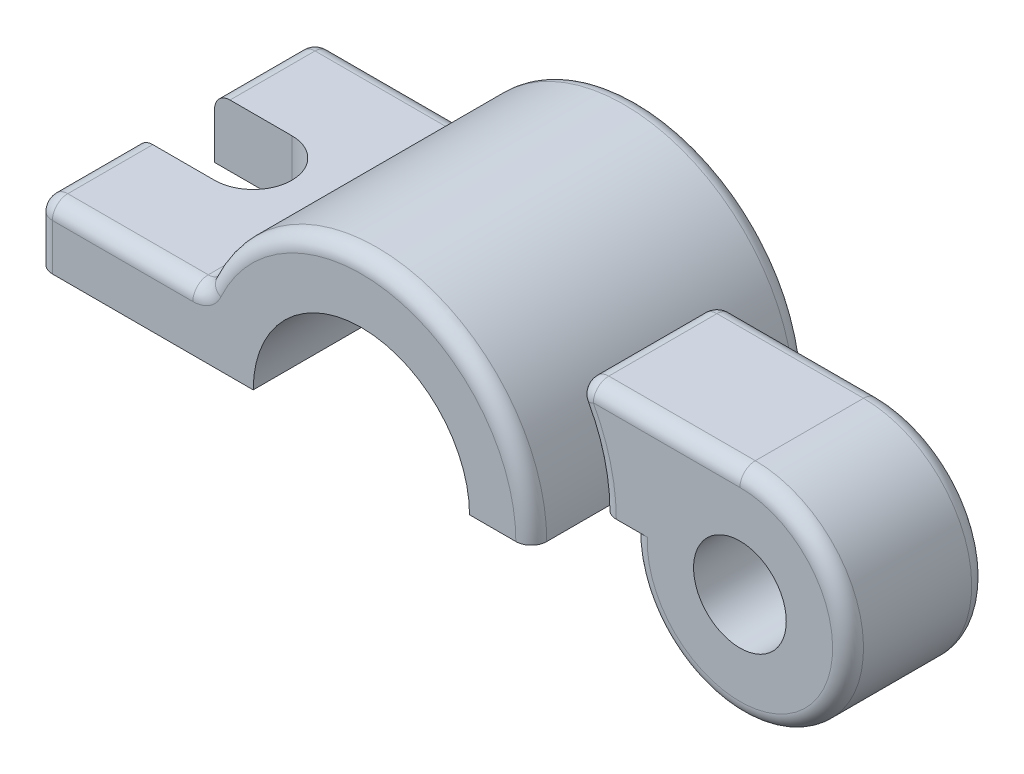
SolidWorks part; units mm, degrees
ref_plane "前基準面" through (0, 0, 0) normal (0, 0, 1) x (1, 0, 0)
ref_plane "上基準面" through (0, 0, 0) normal (0, 1, 0) x (1, 0, 0)
ref_plane "右基準面" through (0, 0, 0) normal (1, 0, 0) x (0, 0, -1)
sketch "草圖1" plane through (0, 0, 0) normal (0, 0, 1) x (1, 0, 0)
  line L0 (14, 0) -> (22, 0)
  line L1 (-14, 0) -> (-42, 0)
  line L2 (-42, 0) -> (-42, 8)
  line L3 (-42, 8) -> (-20.4939, 8)
  arc A0 (14, 0) -> (-14, 0) centre (0, 0) ccw
  arc A1 (22, 0) -> (-20.4939, 8) centre (0, 0) ccw
  dimension "D1" = 14
  dimension "D2" = 22
  dimension "D3" = 8
  dimension "D4" = 42
  dimension "D5" = 8
extrude "填料-伸長1" add sketch "草圖1" along normal mid plane 36
sketch "草圖2" plane through (0, 8, 0) normal (0, 1, 0) x (1, 0, 0)
  line L0 (-42, -5) -> (-42, 5)
  line L2 (-42, -18) -> (-42, 18) construction
  line L3 (-42, 5) -> (-32, 5)
  line L4 (-32, 0) -> (-14.3949, 0) construction
  line L6 (-32, -5) -> (-42, -5)
  line L12 (-20.4939, 18) -> (-42, 18) construction
  line L13 (-20.4939, -18) -> (-42, -18) construction
  arc A0 (-32, 5) -> (-32, -5) centre (-32, 0) cw
  dimension "D1" = 10
  dimension "D2" = 10
sketch "草圖4" plane through (0, 0, 18) normal (0, 0, 1) x (1, 0, 0)
  line L0 (17.3184, 13.5674) -> (40, 13.5674)
  line L1 (26.0067, 0) -> (22, 0)
  line L2 (-42, 8) -> (-42, 0) construction
  arc A0 (22, 0) -> (-20.4939, 8) centre (0, 0) ccw construction
  arc A1 (40, 13.5674) -> (26.0067, 0) centre (40, -0.4326) cw
  circle A2 centre (40, -0.4326) radius 6
  arc M6 (22, 0) -> (-20.4939, 8) centre (0, 0) ccw
  dimension "D1" = 12
  dimension "D2" = 14
  dimension "D3" = 82
extrude "填料-伸長4" add sketch "草圖4" along a picked direction on the side against the normal blind 36 separate body contours A1 L0 L1 A2 M6
sketch "草圖7" plane through (0, 13.5674, 0) normal (0, 1, 0) x (1, 0, 0)
  line L0 (0, 0) -> (36.2413, 0) construction
  line L1 (17.3184, 18) -> (54, 18)
  line L2 (54, 18) -> (54, 9)
  line L3 (54, 9) -> (17.3184, 9)
  line L4 (17.3184, 18) -> (17.3184, -18) construction
  line L5 (17.3184, 9) -> (17.3184, 18)
  line L6 (17.3184, -9) -> (17.3184, -18)
  line L7 (54, -18) -> (54, -9)
  line L8 (54, -9) -> (17.3184, -9)
  line L9 (17.3184, -18) -> (54, -18)
  dimension "D1" = 18
extrude "除料-伸長5" cut sketch "草圖7" against normal up to next
fillet "圓角1" radius 2 8 edges at (4.0703, 21.6202, -18) (4.0703, 21.6202, 18) (-42, 4, -18) (-42, 4, 18) (-31.247, 8, -18) (-42, 8, 0) (-31.247, 8, 18) (-20.4939, 8, 0)
extrude "除料-伸長6" cut sketch "草圖2" against normal through all
fillet "圓角2" radius 2 7 edges at (20.7967, 7.1762, -9) (49.7453, -10.4839, -9) (28.6592, 13.5674, -9) (49.7453, -10.4839, 9) (28.6592, 13.5674, 9) (17.3184, 13.5674, 0) (20.7967, 7.1762, 9)
